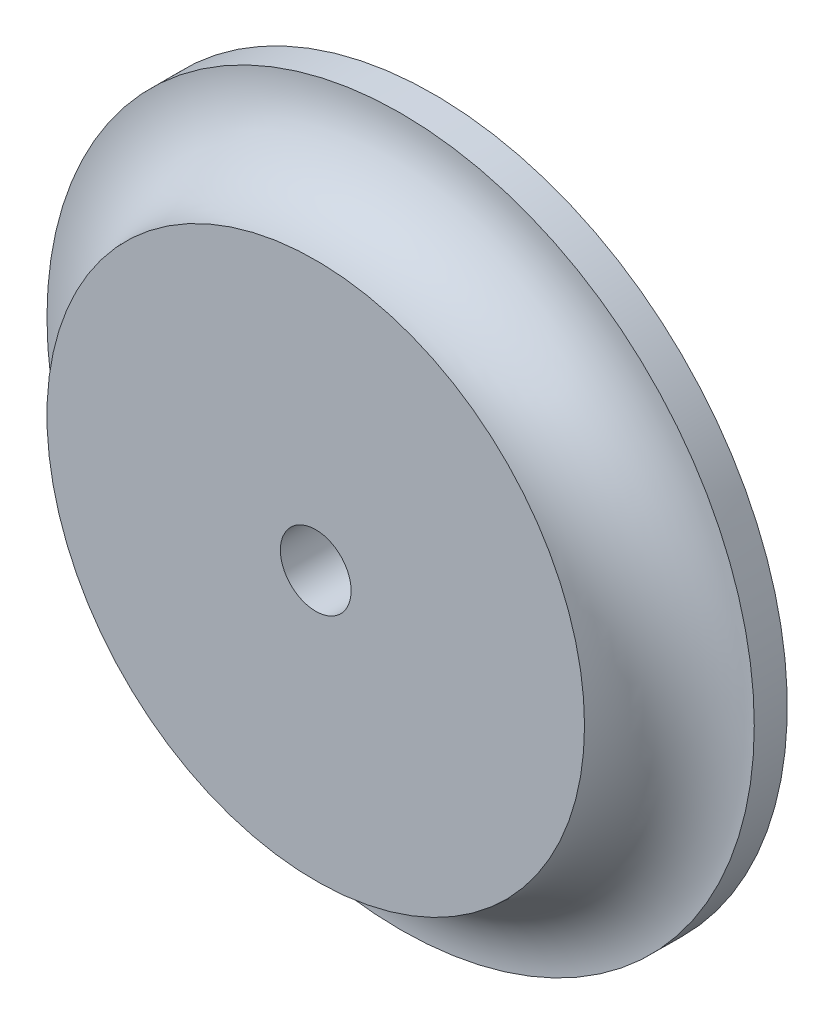
SolidWorks part; units mm, degrees
ref_plane "Front Plane" through (0, 0, 0) normal (0, 0, 1) x (1, 0, 0)
ref_plane "Top Plane" through (0, 0, 0) normal (0, 1, 0) x (1, 0, 0)
ref_plane "Right Plane" through (0, 0, 0) normal (1, 0, 0) x (0, 0, -1)
sketch "Sketch5" plane through (0, 0, 0) normal (0, 1, 0) x (1, 0, 0)
  line L0 (0, 0) -> (-38.1, 0)
  line L1 (-55, 0) -> (55, 0) construction
  line L2 (0, 0) -> (0, 18.288)
  line L3 (0, -55) -> (0, 55) construction
  line L4 (-38.1, 18.288) -> (0, 18.288)
  line L5 (0, 0) -> (0, 18.288) construction
  arc A0 (-38.1, 18.288) -> (-38.1, 0) centre (-38.1, 9.144) cw
  dimension "D1" = 38.1
  dimension "D2" = 18.288
revolve "Revolve1" add sketch "Sketch5" angle 360 about L5
sketch "Sketch9" plane through (0, 0, 0) normal (0, 0, 1) x (1, 0, 0)
  circle A0 centre (0, 0) radius 38.1
extrude "Boss-Extrude2" add sketch "Sketch9" along normal blind 3.556
sketch "Sketch10" plane through (0, 0, -18.288) normal (0, 0, -1) x (-1, 0, 0)
  circle A0 centre (0, 0) radius 38.1
extrude "Boss-Extrude3" add sketch "Sketch10" along normal blind 3.556
hole_wizard "3/4 (0.3) Diameter Hole1" positions "Sketch13" profile "Sketch14" hole size "3/4" standard "ANSI Inch" end condition through all
sketch "Sketch13" plane through (0, 0, 3.556) normal (0, 0, 1) x (1, 0, 0)
  point P0 (0, 0)
sketch "Sketch14" plane through (0, 0, 3.556) normal (1, 0, 0) x (0, -1, 0)
  line L0 (0, 0) -> (0, 25.4)
  line L1 (0, 25.4) -> (3.81, 25.4)
  line L2 (3.81, 25.4) -> (3.81, 0)
  line L5 (3.81, 0) -> (0, 0)
  line L11 (0, -6.35) -> (0, 107.95) construction
  dimension "Thru Hole Dia." = 7.62
  dimension "Thru Hole Depth" = 25.4
sketch "Sketch16" plane through (0, 0, 0) normal (0, 1, 0) x (1, 0, 0)
  line L0 (-38.1, -3.556) -> (38.1, -3.556) construction
  line L1 (-38.1, 9.144) -> (38.1, 9.144)
  line L2 (-38.1, 9.144) -> (-38.1, -3.556)
  line L3 (-38.1, -3.556) -> (38.1, -3.556)
  line L4 (38.1, 9.144) -> (38.1, -3.556)
  line L5 (0, -13.97) -> (0, 13.97) construction
  point P6 (0, 9.144)
  dimension "D1" = 76.2
  dimension "D2" = 12.7
extrude "Cut-Extrude1" cut sketch "Sketch16" against normal through all and the other way through all
